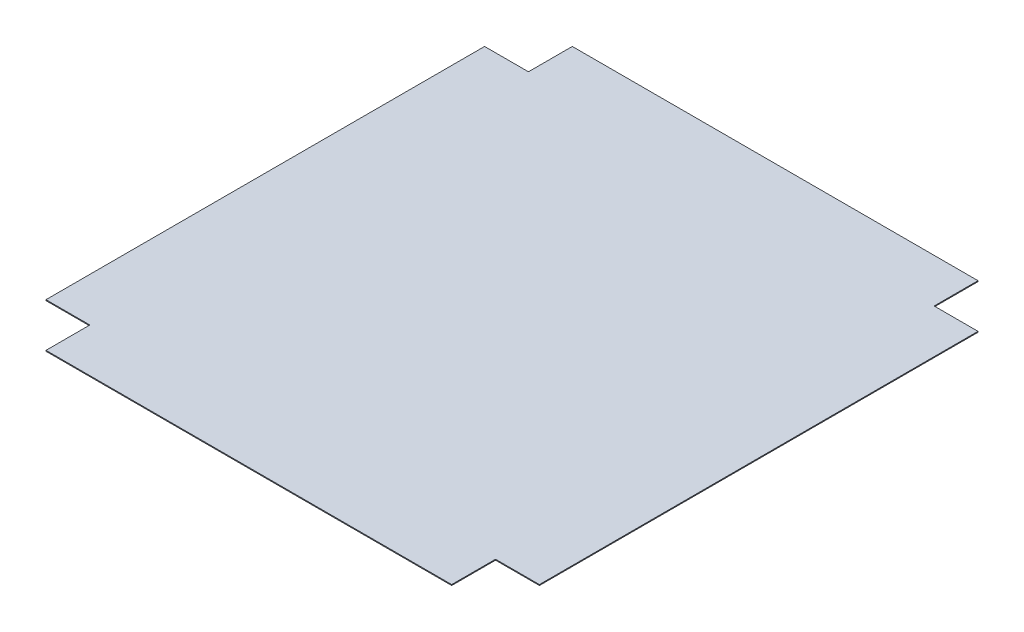
SolidWorks part; units mm, degrees
ref_plane "Front Plane" through (0, 0, 0) normal (0, 0, 1) x (1, 0, 0)
ref_plane "Top Plane" through (0, 0, 0) normal (0, 1, 0) x (1, 0, 0)
ref_plane "Right Plane" through (0, 0, 0) normal (1, 0, 0) x (0, 0, -1)
sketch "Sketch1" plane through (0, 0, 0) normal (0, 1, 0) x (1, 0, 0)
  line L0 (-186.1323, 0) -> (208.1332, 0) construction
  line L1 (0, 138.0494) -> (0, -152.7145) construction
  line L2 (-92.5, 139.7908) -> (-92.5, -157.4501) construction
  line L3 (-112.5, 120) -> (112.5, 120) construction
  line L4 (-112.5, 120) -> (-112.5, -120) construction
  line L5 (-112.5, -120) -> (112.5, -120) construction
  line L6 (112.5, 120) -> (112.5, -120) construction
  line L7 (-125.7048, 100) -> (122.1347, 100) construction
  line L8 (92.5, 139.7908) -> (92.5, -157.4501) construction
  line L9 (-125.7048, -100) -> (122.1347, -100) construction
  line L10 (-92.5, 120) -> (-92.5, 100)
  line L11 (-92.5, 100) -> (-112.5, 100)
  line L12 (-92.5, 120) -> (92.5, 120)
  line L13 (92.5, 120) -> (92.5, 100)
  line L14 (92.5, 100) -> (112.5, 100)
  line L15 (112.5, 100) -> (112.5, -100)
  line L16 (112.5, -100) -> (92.5, -100)
  line L17 (92.5, -100) -> (92.5, -120)
  line L18 (92.5, -120) -> (-92.5, -120)
  line L19 (-92.5, -120) -> (-92.5, -100)
  line L20 (-92.5, -100) -> (-112.5, -100)
  line L21 (-112.5, -100) -> (-112.5, 100)
  point P9 (0, 120)
  point P10 (112.5, 0)
  dimension "D1" = 240
  dimension "D2" = 225
  dimension "D3" = 20
  dimension "D4" = 20
extrude "Boss-Extrude1" add sketch "Sketch1" along normal blind 0.4064
